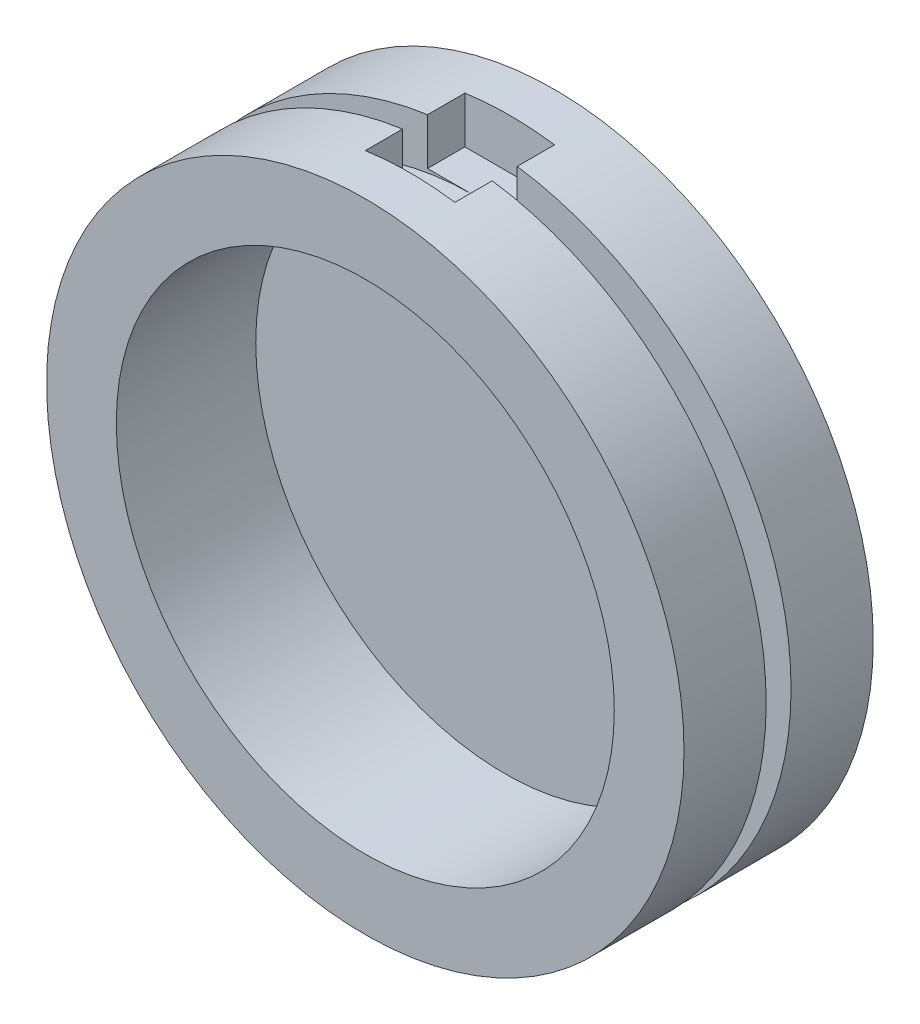
SolidWorks part; units mm, degrees
ref_plane "Front Plane" through (0, 0, 0) normal (0, 0, 1) x (1, 0, 0)
ref_plane "Top Plane" through (0, 0, 0) normal (0, 1, 0) x (1, 0, 0)
ref_plane "Right Plane" through (0, 0, 0) normal (1, 0, 0) x (0, 0, -1)
sketch "Sketch2" plane through (0, 0, 0) normal (1, 0, 0) x (0, 0, -1)
  line L0 (0, 0) -> (0, 32)
  line L1 (0, 32) -> (-8.25, 32)
  line L2 (-19, 32) -> (-19, 25)
  line L3 (-19, 25) -> (-5, 25)
  line L4 (-5, 25) -> (-5, 0)
  line L5 (-5, 0) -> (0, 0)
  line L6 (-8.25, 32) -> (-8.25, 27)
  line L7 (-8.25, 27) -> (-10.75, 27)
  line L8 (-10.75, 27) -> (-10.75, 32)
  line L9 (-10.75, 32) -> (-19, 32)
  dimension "D1" = 19
  dimension "D2" = 32
  dimension "D3" = 7
  dimension "D4" = 5
  dimension "D5" = 2.5
  dimension "D6" = 8.25
  dimension "D7" = 5
revolve "Revolve1" add sketch "Sketch2" angle 360 about L5
ref_plane "Plane1" through (0, 32, 0) normal (0, 1, 0) x (1, 0, 0)
sketch "Sketch7" plane through (0, 32, 0) normal (0, 1, 0) x (1, 0, 0)
  line L1 (-4.5, -14.5) -> (4.5, -14.5)
  line L2 (-4.5, -14.5) -> (-4.5, -4.5)
  line L3 (-4.5, -4.5) -> (4.5, -4.5)
  line L4 (4.5, -14.5) -> (4.5, -4.5)
  line L5 (-4.5, -9.5) -> (4.5, -9.5) construction
  line L6 (32, 0) -> (-32, 0) construction
  line L7 (0, -4.5) -> (0, 0) construction
  dimension "D1" = 9.5
  dimension "D2" = 10
  dimension "D3" = 9
extrude "Cut-Extrude1" cut sketch "Sketch7" against normal blind 5
mirror "Mirror1" about plane through (0, 0, 0) normal (0, 1, 0) of "Cut-Extrude1"
